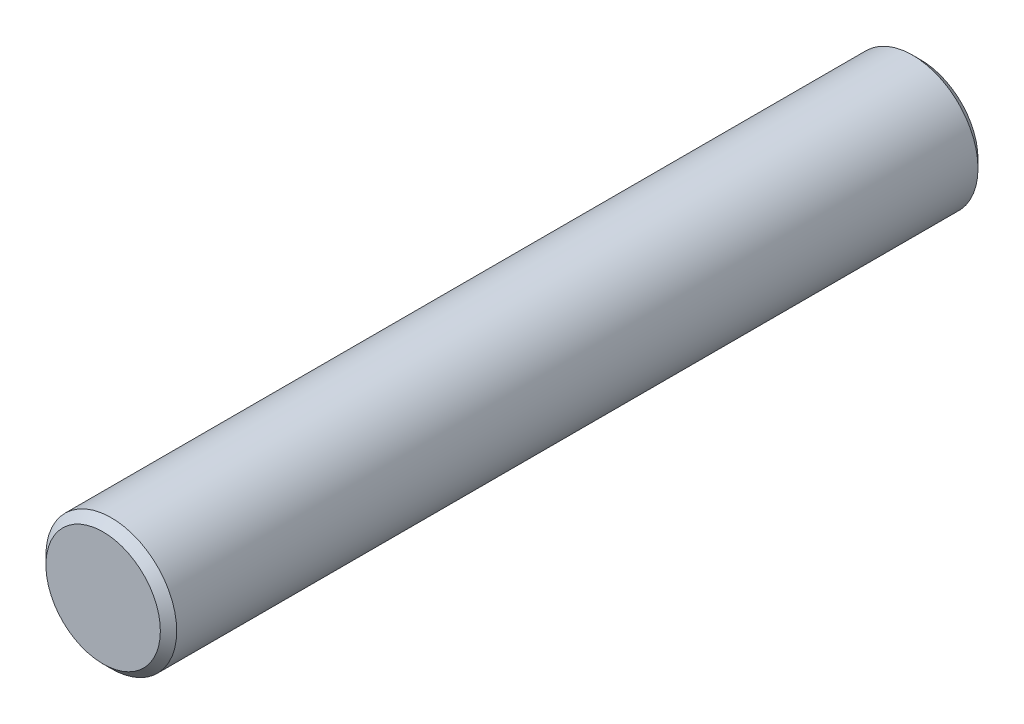
SolidWorks part; units mm, degrees
ref_plane "Front Plane" through (0, 0, 0) normal (0, 0, 1) x (1, 0, 0)
ref_plane "Top Plane" through (0, 0, 0) normal (0, 1, 0) x (1, 0, 0)
ref_plane "Right Plane" through (0, 0, 0) normal (1, 0, 0) x (0, 0, -1)
sketch "Sketch1" plane through (0, 0, 0) normal (0, 0, 1) x (1, 0, 0)
  circle A0 centre (0, 0) radius 4
  dimension "D1" = 8
extrude "Corpo" add sketch "Sketch1" against normal blind 50
chamfer "Quebra de Canto" distance 0.5 angle 45 2 edges at (4, 0, -50) (4, 0, 0)
